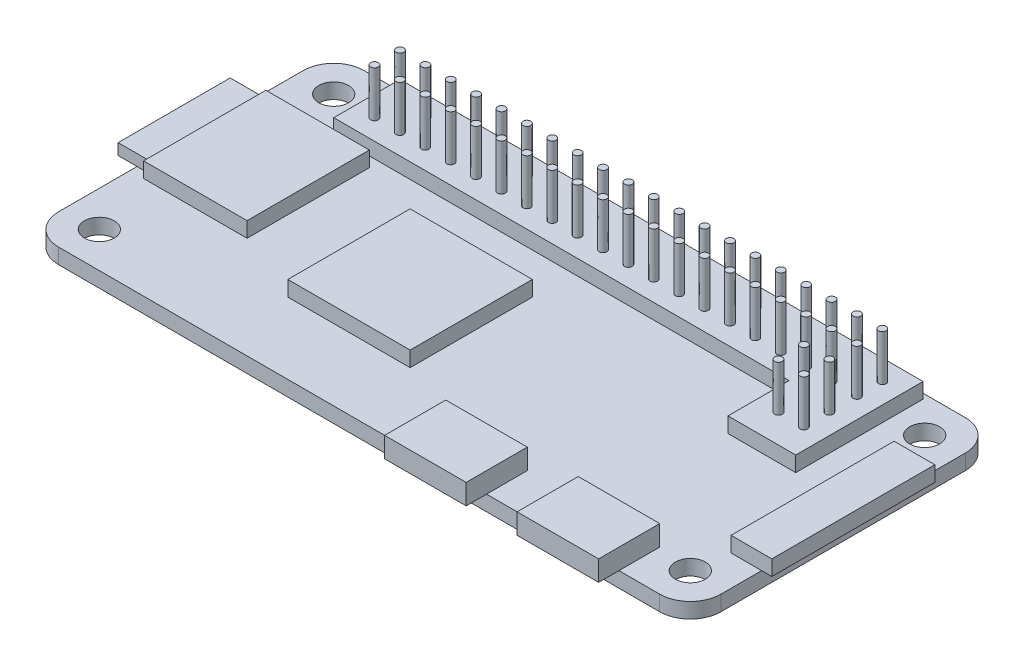
SolidWorks part; units mm, degrees
ref_plane "Front Plane" through (0, 0, 0) normal (0, 0, 1) x (1, 0, 0)
ref_plane "Top Plane" through (0, 0, 0) normal (0, 1, 0) x (1, 0, 0)
ref_plane "Right Plane" through (0, 0, 0) normal (1, 0, 0) x (0, 0, -1)
sketch "Sketch1" plane through (0, 0, 0) normal (0, 1, 0) x (1, 0, 0)
  line L1 (-29.5, 15) -> (29.5, 15)
  line L2 (-32.5, 12) -> (-32.5, -12)
  line L3 (-29.5, -15) -> (29.5, -15)
  line L4 (32.5, 12) -> (32.5, -12)
  line L5 (-32.5, 15) -> (32.5, -15) construction
  line L6 (-32.5, -15) -> (32.5, 15) construction
  arc A0 (29.5, 15) -> (32.5, 12) centre (29.5, 12) cw
  arc A1 (29.5, -15) -> (32.5, -12) centre (29.5, -12) ccw
  arc A2 (-32.5, -12) -> (-29.5, -15) centre (-29.5, -12) ccw
  arc A3 (-29.5, 15) -> (-32.5, 12) centre (-29.5, 12) ccw
  point P0 (0, 0)
  dimension "D1" = 3
  dimension "D2" = 65
  dimension "D3" = 30
extrude "Boss-Extrude1" add sketch "Sketch1" along normal blind 1.5
sketch "Sketch2" plane through (0, 1.5, 0) normal (0, 1, 0) x (1, 0, 0)
  line L0 (-32.5, 12) -> (-32.5, -12) construction
  line L1 (29.5, 15) -> (-29.5, 15) construction
  line L2 (0, 15) -> (0, -15) construction
  line L3 (-29.5, -15) -> (29.5, -15) construction
  line L4 (-32.5, 0) -> (32.5, 0) construction
  line L5 (32.5, -12) -> (32.5, 12) construction
  circle A0 centre (-29, 11.5) radius 1.4674
  circle A1 centre (29, 11.5) radius 1.4674
  circle A2 centre (29, -11.5) radius 1.4674
  circle A3 centre (-29, -11.5) radius 1.4674
  dimension "D1" = 3.5
  dimension "D2" = 3.5
extrude "Cut-Extrude1" cut sketch "Sketch2" against normal up to next
sketch "Sketch3" plane through (0, 1.5, 0) normal (0, 1, 0) x (1, 0, 0)
  line L0 (29.5, 15) -> (-29.5, 15) construction
  line L1 (-31.1572, 7) -> (-20.9996, 7)
  line L2 (-31.1572, 7) -> (-31.1572, -5)
  line L3 (-31.1572, -5) -> (-20.9996, -5)
  line L4 (-20.9996, 7) -> (-20.9996, -5)
  line L5 (-25.4947, 14.5) -> (25.8458, 14.5)
  line L6 (-25.4947, 14.5) -> (-25.4947, 8)
  line L7 (-25.4947, 8) -> (19.1958, 8)
  line L8 (25.8458, 14.5) -> (25.8458, 8)
  line L9 (-29.5, -15) -> (29.5, -15) construction
  line L10 (29.5, 8) -> (33.5, 8)
  line L11 (29.5, 8) -> (29.5, -8)
  line L12 (29.5, -8) -> (33.5, -8)
  line L13 (33.5, 8) -> (33.5, -8)
  line L14 (32.5, -12) -> (32.5, 12) construction
  line L16 (-13.9996, 4) -> (-1.9996, 4)
  line L17 (-13.9996, 4) -> (-13.9996, -8)
  line L18 (-13.9996, -8) -> (-1.9996, -8)
  line L19 (-1.9996, 4) -> (-1.9996, -8)
  line L21 (25.8458, 8) -> (25.8458, 2)
  line L22 (25.8458, 2) -> (19.1958, 2)
  line L23 (19.1958, 8) -> (19.1958, 2)
  dimension "D1" = 0.5
  dimension "D2" = 7
  dimension "D3" = 12
  dimension "D4" = 8
  dimension "D5" = 7
  dimension "D6" = 7
  dimension "D7" = 4
  dimension "D8" = 1
  dimension "D9" = 4
  dimension "D10" = 12
  dimension "D11" = 12
  dimension "D12" = 7
  dimension "D13" = 6
  dimension "D14" = 6.6542
  dimension "D15" = 6.65
extrude "Boss-Extrude2" add sketch "Sketch3" along normal blind 1.5
sketch "Sketch5" plane through (0, 3, 0) normal (0, 1, 0) x (1, 0, 0)
  line L3 (-23.4947, 12.5) -> (-23.4947, 14.5) construction
  line L4 (25.8458, 14.5) -> (-25.4947, 14.5) construction
  line L5 (-23.4947, 10) -> (-23.4947, 8) construction
  line L6 (-25.4947, 8) -> (19.1958, 8) construction
  line L7 (-25.4947, 14.5) -> (-25.4947, 8) construction
  line L8 (25.8458, 2) -> (25.8458, 14.5) construction
  circle A0 centre (-23.4947, 12.5) radius 0.375
  circle A1 centre (-21.0031, 12.5) radius 0.375
  circle A2 centre (-18.5115, 12.5) radius 0.375
  circle A3 centre (-16.0199, 12.5) radius 0.375
  circle A4 centre (-13.5283, 12.5) radius 0.375
  circle A5 centre (-11.0367, 12.5) radius 0.375
  circle A6 centre (-8.5451, 12.5) radius 0.375
  circle A7 centre (-6.0535, 12.5) radius 0.375
  circle A8 centre (-3.5619, 12.5) radius 0.375
  circle A9 centre (-1.0703, 12.5) radius 0.375
  circle A10 centre (1.4213, 12.5) radius 0.375
  circle A11 centre (3.913, 12.5) radius 0.375
  circle A12 centre (6.4046, 12.5) radius 0.375
  circle A13 centre (8.8962, 12.5) radius 0.375
  circle A14 centre (11.3878, 12.5) radius 0.375
  circle A15 centre (13.8794, 12.5) radius 0.375
  circle A16 centre (16.371, 12.5) radius 0.375
  circle A17 centre (18.8626, 12.5) radius 0.375
  circle A18 centre (21.3542, 12.5) radius 0.375
  circle A19 centre (23.8458, 12.5) radius 0.375
  circle A20 centre (-21.0031, 10) radius 0.375
  circle A21 centre (-18.5115, 10) radius 0.375
  circle A22 centre (-16.0199, 10) radius 0.375
  circle A23 centre (-13.5283, 10) radius 0.375
  circle A24 centre (-11.0367, 10) radius 0.375
  circle A25 centre (-8.5451, 10) radius 0.375
  circle A26 centre (-6.0535, 10) radius 0.375
  circle A27 centre (-3.5619, 10) radius 0.375
  circle A28 centre (-1.0703, 10) radius 0.375
  circle A29 centre (1.4213, 10) radius 0.375
  circle A30 centre (3.913, 10) radius 0.375
  circle A31 centre (6.4046, 10) radius 0.375
  circle A32 centre (8.8962, 10) radius 0.375
  circle A33 centre (11.3878, 10) radius 0.375
  circle A34 centre (13.8794, 10) radius 0.375
  circle A35 centre (16.371, 10) radius 0.375
  circle A36 centre (18.8626, 10) radius 0.375
  circle A37 centre (21.3542, 10) radius 0.375
  circle A38 centre (23.8458, 10) radius 0.375
  circle A39 centre (-23.4947, 10) radius 0.375
  circle A40 centre (21.3542, 4.8) radius 0.375
  circle A41 centre (21.3542, 7.3) radius 0.375
  circle A42 centre (23.8458, 7.3) radius 0.375
  circle A43 centre (23.8458, 4.8) radius 0.375
  dimension "D1" = 0.75
  dimension "D4" = 2
  dimension "D5" = 2
  dimension "D2" = 20
  dimension "D3" = 2
  dimension "D6" = 2
extrude "Boss-Extrude3" add sketch "Sketch5" along normal blind 4.5
sketch "Sketch6" plane through (-31.1572, 0, 0) normal (-1, 0, 0) x (0, 0, 1)
  line L0 (-7, 3) -> (-7, 1.5) construction
  line L1 (-6.5, 1.7) -> (4.5, 1.7)
  line L2 (-6.5, 1.7) -> (-6.5, 2.8)
  line L3 (-6.5, 2.8) -> (4.5, 2.8)
  line L4 (4.5, 1.7) -> (4.5, 2.8)
  line L5 (5, 3) -> (5, 1.5) construction
  line L6 (-7, 1.5) -> (5, 1.5) construction
  line L7 (-7, 3) -> (5, 3) construction
  dimension "D1" = 0.5
  dimension "D2" = 0.5
  dimension "D3" = 0.2
  dimension "D4" = 0.2
extrude "Boss-Extrude4" add sketch "Sketch6" along normal blind 3
sketch "Sketch7" [suppressed] plane through (0, 3, 0) normal (0, 1, 0) x (1, 0, 0)
  line L0 (25.8458, 2) -> (25.8458, 14.5) construction
  line L5 (25.8458, 14.5) -> (-25.4947, 14.5) construction
  line L6 (-25.4947, 14.5) -> (-25.4947, 8) construction
  line L7 (-25.4947, 8) -> (19.1958, 8) construction
  line L8 (19.1958, 8) -> (19.1958, 2) construction
  line L9 (19.1958, 2) -> (25.8458, 2) construction
  line L10 (25.8458, 2) -> (25.8458, 14.5)
  line L11 (25.8458, 14.5) -> (-25.4947, 14.5)
  line L12 (-25.4947, 14.5) -> (-25.4947, 8)
  line L13 (-25.4947, 8) -> (19.1958, 8)
  line L14 (19.1958, 8) -> (19.1958, 2)
  line L15 (19.1958, 2) -> (25.8458, 2)
extrude "Cut-Extrude2" [suppressed] cut sketch "Sketch7" along normal up to surface and the other way up to surface
sketch "Sketch8" plane through (0, 1.5, 0) normal (0, 1, 0) x (1, 0, 0)
  circle A0 centre (23.8458, 4.8) radius 0.375 construction
  circle A1 centre (-11.0367, 12.5) radius 0.375
  circle A2 centre (-11.0367, 12.5) radius 0.375
  circle A3 centre (-13.5283, 12.5) radius 0.375
  circle A4 centre (-13.5283, 12.5) radius 0.375
  circle A5 centre (-16.0199, 12.5) radius 0.375
  circle A6 centre (-16.0199, 12.5) radius 0.375
  circle A7 centre (-18.5115, 12.5) radius 0.375
  circle A8 centre (-18.5115, 12.5) radius 0.375
  circle A9 centre (-21.0031, 12.5) radius 0.375
  circle A10 centre (-21.0031, 12.5) radius 0.375
  circle A11 centre (-23.4947, 12.5) radius 0.375
  circle A12 centre (-23.4947, 12.5) radius 0.375
  circle A13 centre (8.8962, 12.5) radius 0.375
  circle A14 centre (8.8962, 12.5) radius 0.375
  circle A15 centre (6.4046, 12.5) radius 0.375
  circle A16 centre (6.4046, 12.5) radius 0.375
  circle A17 centre (3.913, 12.5) radius 0.375
  circle A18 centre (3.913, 12.5) radius 0.375
  circle A19 centre (1.4213, 12.5) radius 0.375
  circle A20 centre (1.4213, 12.5) radius 0.375
  circle A21 centre (-1.0703, 12.5) radius 0.375
  circle A22 centre (-1.0703, 12.5) radius 0.375
  circle A23 centre (-3.5619, 12.5) radius 0.375
  circle A24 centre (-3.5619, 12.5) radius 0.375
  circle A25 centre (-6.0535, 12.5) radius 0.375
  circle A26 centre (-6.0535, 12.5) radius 0.375
  circle A27 centre (-8.5451, 12.5) radius 0.375
  circle A28 centre (-8.5451, 12.5) radius 0.375
  circle A29 centre (-18.5115, 10) radius 0.375
  circle A30 centre (-18.5115, 10) radius 0.375
  circle A31 centre (-21.0031, 10) radius 0.375
  circle A32 centre (-21.0031, 10) radius 0.375
  circle A33 centre (23.8458, 12.5) radius 0.375
  circle A34 centre (23.8458, 12.5) radius 0.375
  circle A35 centre (21.3542, 12.5) radius 0.375
  circle A36 centre (21.3542, 12.5) radius 0.375
  circle A37 centre (18.8626, 12.5) radius 0.375
  circle A38 centre (18.8626, 12.5) radius 0.375
  circle A39 centre (16.371, 12.5) radius 0.375
  circle A40 centre (16.371, 12.5) radius 0.375
  circle A41 centre (13.8794, 12.5) radius 0.375
  circle A42 centre (13.8794, 12.5) radius 0.375
  circle A43 centre (11.3878, 12.5) radius 0.375
  circle A44 centre (11.3878, 12.5) radius 0.375
  circle A45 centre (1.4213, 10) radius 0.375
  circle A46 centre (1.4213, 10) radius 0.375
  circle A47 centre (-1.0703, 10) radius 0.375
  circle A48 centre (-1.0703, 10) radius 0.375
  circle A49 centre (-3.5619, 10) radius 0.375
  circle A50 centre (-3.5619, 10) radius 0.375
  circle A51 centre (-6.0535, 10) radius 0.375
  circle A52 centre (-6.0535, 10) radius 0.375
  circle A53 centre (-8.5451, 10) radius 0.375
  circle A54 centre (-8.5451, 10) radius 0.375
  circle A55 centre (-11.0367, 10) radius 0.375
  circle A56 centre (-11.0367, 10) radius 0.375
  circle A57 centre (-13.5283, 10) radius 0.375
  circle A58 centre (-13.5283, 10) radius 0.375
  circle A59 centre (-16.0199, 10) radius 0.375
  circle A60 centre (-16.0199, 10) radius 0.375
  circle A61 centre (21.3542, 10) radius 0.375
  circle A62 centre (21.3542, 10) radius 0.375
  circle A63 centre (18.8626, 10) radius 0.375
  circle A64 centre (18.8626, 10) radius 0.375
  circle A65 centre (16.371, 10) radius 0.375
  circle A66 centre (16.371, 10) radius 0.375
  circle A67 centre (13.8794, 10) radius 0.375
  circle A68 centre (13.8794, 10) radius 0.375
  circle A69 centre (11.3878, 10) radius 0.375
  circle A70 centre (11.3878, 10) radius 0.375
  circle A71 centre (8.8962, 10) radius 0.375
  circle A72 centre (8.8962, 10) radius 0.375
  circle A73 centre (6.4046, 10) radius 0.375
  circle A74 centre (6.4046, 10) radius 0.375
  circle A75 centre (3.913, 10) radius 0.375
  circle A76 centre (3.913, 10) radius 0.375
  circle A77 centre (-23.4947, 10) radius 0.375
  circle A78 centre (-23.4947, 10) radius 0.375
  circle A79 centre (23.8458, 10) radius 0.375
  circle A80 centre (23.8458, 10) radius 0.375
  circle A81 centre (21.3542, 4.8) radius 0.375 construction
  circle A82 centre (21.3542, 7.3) radius 0.375 construction
  circle A83 centre (23.8458, 7.3) radius 0.375 construction
  circle A84 centre (23.8458, 4.8) radius 0.375
  circle A85 centre (21.3542, 4.8) radius 0.375
  circle A86 centre (21.3542, 7.3) radius 0.375
  circle A87 centre (23.8458, 7.3) radius 0.375
  dimension "D1" = 0
  dimension "D2" = 0
  dimension "D3" = 0
  dimension "D4" = 0
  dimension "D5" = 0
  dimension "D6" = 0
  dimension "D7" = 0
  dimension "D8" = 0
  dimension "D9" = 0
  dimension "D10" = 0
  dimension "D11" = 0
  dimension "D12" = 0
  dimension "D13" = 0
  dimension "D14" = 0
  dimension "D15" = 0
  dimension "D16" = 0
  dimension "D17" = 0
  dimension "D18" = 0
  dimension "D19" = 0
  dimension "D20" = 0
  dimension "D21" = 0
  dimension "D22" = 0
  dimension "D23" = 0
  dimension "D24" = 0
  dimension "D25" = 0
  dimension "D26" = 0
  dimension "D27" = 0
  dimension "D28" = 0
  dimension "D29" = 0
  dimension "D30" = 0
  dimension "D31" = 0
  dimension "D32" = 0
  dimension "D33" = 0
  dimension "D34" = 0
  dimension "D35" = 0
  dimension "D36" = 0
  dimension "D37" = 0
  dimension "D38" = 0
  dimension "D39" = 0
  dimension "D40" = 0
extrude "Cut-Extrude3" cut sketch "Sketch8" against normal up to next (1.5 mm away)
sketch "Sketch9" plane through (0, 1.5, 0) normal (0, 1, 0) x (1, 0, 0)
  line L1 (17.5, -11) -> (25.5, -11)
  line L2 (17.5, -11) -> (17.5, -17)
  line L3 (17.5, -17) -> (25.5, -17)
  line L4 (25.5, -11) -> (25.5, -17)
  line L5 (32.5, -12) -> (32.5, -8) construction
  line L6 (-29.5, -15) -> (29.5, -15) construction
  dimension "D1" = 15
  dimension "D2" = 7
  dimension "D3" = 2
  dimension "D4" = 4
extrude "Boss-Extrude5" add sketch "Sketch9" along normal blind 2
pattern_linear "LPattern1" count 2 spacing 13 along (-1, 0, 0) of "Boss-Extrude5"
